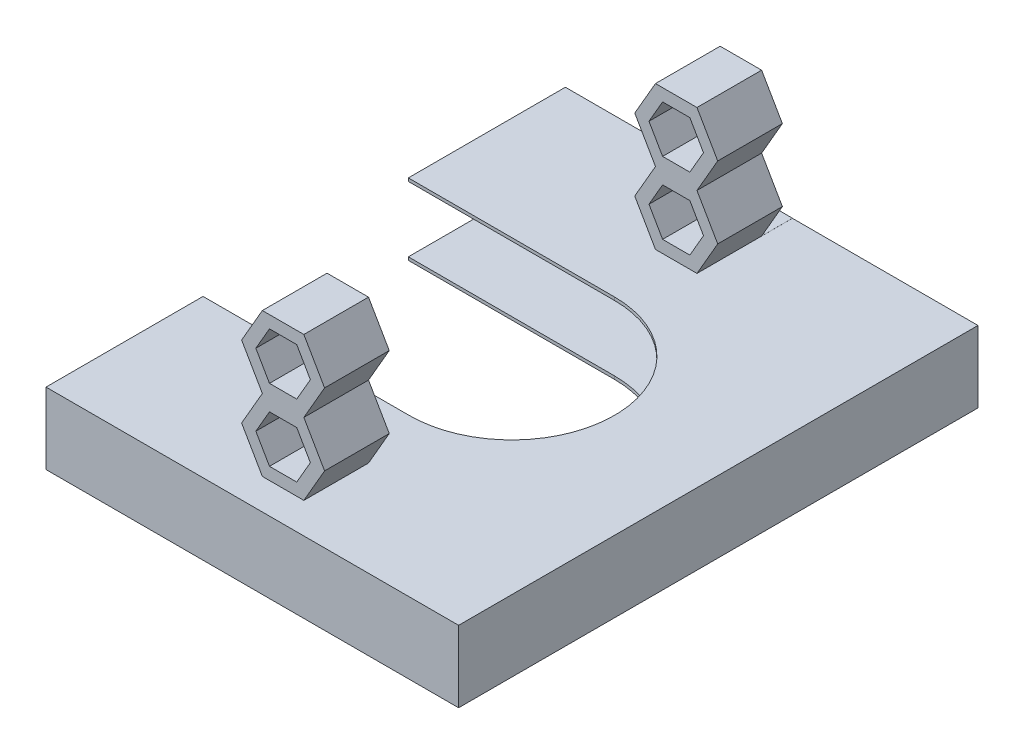
SolidWorks part; units mm, degrees
ref_plane "Front Plane" through (0, 0, 0) normal (0, 0, 1) x (1, 0, 0)
ref_plane "Top Plane" through (0, 0, 0) normal (0, 1, 0) x (1, 0, 0)
ref_plane "Right Plane" through (0, 0, 0) normal (1, 0, 0) x (0, 0, -1)
sketch "Sketch2" plane through (0, 0, 0) normal (0, 0, 1) x (1, 0, 0)
  line L0 (3.0311, 2.5013) -> (4.0415, 2.5013)
  line L1 (4.0415, 4.2513) -> (3.0311, 6.0013)
  line L2 (0, 0) -> (4.0415, 0)
  line L3 (0, 0) -> (0, 2.5013)
  line L4 (0, 2.5013) -> (1.0104, 2.5013)
  line L5 (4.0415, 0) -> (4.0415, 2.5013)
  line L7 (1.0104, 6.0013) -> (0, 4.2513)
  line L8 (0, 4.2513) -> (1.0104, 2.5013)
  line L10 (3.0311, 2.5013) -> (4.0415, 4.2513)
  line L11 (4.0415, 7.7513) -> (3.0311, 9.5013)
  line L12 (3.0311, 9.5013) -> (1.0104, 9.5013)
  line L13 (1.0104, 9.5013) -> (0, 7.7513)
  line L14 (0, 7.7513) -> (1.0104, 6.0013)
  line L16 (3.0311, 6.0013) -> (4.0415, 7.7513)
  line L17 (2.0207, 6.0013) -> (3.0311, 6.0013) [skipped]
  line L18 (3.0311, 6.0013) -> (2.0207, 6.0013) [skipped]
  line L19 (2.0207, 2.5013) -> (3.0311, 2.5013) [skipped]
  circle A0 centre (2.0207, 4.2513) radius 1.75 construction
  circle A1 centre (2.0207, 7.7513) radius 1.75 construction
extrude "Boss-Extrude1" add sketch "Sketch2" along normal blind 25.3 contours L1 L16 L11 L12 L13 L14 L7 L8 L4 L3 L2 L5 L0 L10
sketch "Sketch3" plane through (0, 0, 25.3) normal (0, 0, 1) x (1, 0, 0)
  line L0 (1.0104, 9.5013) -> (0, 7.7513) construction
  line L1 (3.3486, 7.7513) -> (2.6847, 8.9013)
  line L2 (2.6847, 8.9013) -> (1.3568, 8.9013)
  line L3 (1.3568, 8.9013) -> (0.6928, 7.7513)
  line L4 (0.6928, 7.7513) -> (1.3568, 6.6013)
  line L5 (1.3568, 6.6013) -> (2.6847, 6.6013)
  line L6 (2.6847, 6.6013) -> (3.3486, 7.7513)
  line L7 (3.0311, 6.0013) -> (4.0415, 7.7513) construction
  line L8 (4.0415, 7.7513) -> (3.0311, 9.5013) construction
  line L11 (3.3486, 4.2513) -> (2.6847, 5.4013)
  line L12 (2.6847, 5.4013) -> (1.3568, 5.4013)
  line L13 (1.3568, 5.4013) -> (0.6928, 4.2513)
  line L14 (0.6928, 4.2513) -> (1.3568, 3.1013)
  line L15 (1.3568, 3.1013) -> (2.6847, 3.1013)
  line L16 (2.6847, 3.1013) -> (3.3486, 4.2513)
  line L17 (1.0104, 6.0013) -> (0, 4.2513) construction
  line L18 (0, 4.2513) -> (1.0104, 2.5013) construction
  line L19 (4.0415, 4.2513) -> (3.0311, 6.0013) construction
  circle A0 centre (2.0207, 7.7513) radius 1.15 construction
  circle A1 centre (2.0207, 4.2513) radius 1.15 construction
  dimension "D1" = 0.6
  dimension "D2" = 0.6
  dimension "D3" = 0.6
  dimension "D4" = 0.6
  dimension "D5" = 0.6
  dimension "D6" = 0.6
extrude "Cut-Extrude1" cut sketch "Sketch3" against normal blind 25.3
sketch "Sketch14" plane through (0, 0, 0) normal (0, 0, -1) x (-1, 0, 0)
  line L1 (-4.2364, 9.6861) -> (0.2393, 9.6861)
  line L2 (-4.2364, 9.6861) -> (-4.2364, 2.5073)
  line L3 (-4.2364, 2.5073) -> (0.2393, 2.5073)
  line L4 (0.2393, 9.6861) -> (0.2393, 2.5073)
extrude "Cut-Extrude6" cut sketch "Sketch14" against normal blind 1.5
sketch "Sketch15" plane through (0, 0, 25.3) normal (0, 0, 1) x (1, 0, 0)
  line L1 (0, 9.6086) -> (4.0415, 9.6086)
  line L2 (0, 9.6086) -> (0, 2.5013)
  line L3 (0, 2.5013) -> (4.0415, 2.5013)
  line L4 (4.0415, 9.6086) -> (4.0415, 2.5013)
extrude "Cut-Extrude7" cut sketch "Sketch15" against normal blind 1.5
sketch "Sketch16" plane through (0, 9.5013, 0) normal (0, 1, 0) x (1, 0, 0)
  line L1 (-0.7522, -4.65) -> (4.5577, -4.65)
  line L2 (-0.7522, -4.65) -> (-0.7522, -20.65)
  line L3 (-0.7522, -20.65) -> (4.5577, -20.65)
  line L4 (4.5577, -4.65) -> (4.5577, -20.65)
  line L6 (1.0104, -1.5) -> (3.0311, -1.5) construction
  line L7 (3.0311, -23.8) -> (1.0104, -23.8) construction
  point P4 (1.9027, -4.65)
  dimension "D1" = 16
  dimension "D2" = 3.15
  dimension "D3" = 3.15
extrude "Cut-Extrude8" cut sketch "Sketch16" against normal blind 7
sketch "Sketch17" plane through (4.0415, 0, 0) normal (1, 0, 0) x (0, 0, -1)
  line L1 (-25.3, 2.5013) -> (0, 2.5013)
  line L2 (-25.3, 2.5013) -> (-25.3, 0)
  line L3 (-25.3, 0) -> (0, 0)
  line L4 (0, 2.5013) -> (0, 0)
extrude "Boss-Extrude2" add sketch "Sketch17" along normal blind 8.0293
sketch "Sketch18" plane through (0, 0, 0) normal (-1, 0, 0) x (0, 0, 1)
  line L1 (0, 0) -> (25.3, 0)
  line L2 (0, 0) -> (0, 2.5013)
  line L3 (0, 2.5013) -> (25.3, 2.5013)
  line L4 (25.3, 0) -> (25.3, 2.5013)
extrude "Boss-Extrude3" add sketch "Sketch18" along normal blind 8.0293
sketch "Sketch20" plane through (0, 0, 0) normal (0, -1, 0) x (1, 0, 0)
  line L1 (-8.0293, 0) -> (12.0707, 0)
  line L2 (-8.0293, 0) -> (-8.0293, 25.3)
  line L3 (-8.0293, 25.3) -> (12.0707, 25.3)
  line L4 (12.0707, 0) -> (12.0707, 25.3)
extrude "Boss-Extrude4" add sketch "Sketch20" along normal blind 0.9787
sketch "Sketch21" plane through (0, 2.5013, 0) normal (0, 1, 0) x (1, 0, 0)
  line L2 (-8.0293, -25.3) -> (-8.0293, 0) construction
  line L3 (-8.0293, -7.65) -> (2.0107, -7.65)
  line L4 (-8.0293, -7.65) -> (-8.0293, -17.65)
  line L5 (-8.0293, -17.65) -> (2.0107, -17.65)
  arc A0 (2.0107, -17.65) -> (2.0107, -7.65) centre (2.0107, -12.65) ccw
extrude "Cut-Extrude9" cut sketch "Sketch21" against normal blind 3.48 contours A0 L3 L4 L5
sketch "Sketch22" plane through (-8.0293, 0, 0) normal (-1, 0, 0) x (0, 0, 1)
  line L0 (7.65, 2.5013) -> (0, 2.5013) construction
  line L1 (0.15, -0.8287) -> (25.15, -0.8287)
  line L2 (0.15, -0.8287) -> (0.15, 2.3513)
  line L3 (0.15, 2.3513) -> (25.15, 2.3513)
  line L4 (25.15, -0.8287) -> (25.15, 2.3513)
  line L5 (0, 2.5013) -> (0, -0.9787) construction
  dimension "D1" = 25
  dimension "D2" = 3.18
  dimension "D3" = 0.15
  dimension "D4" = 0.15
extrude "Cut-Extrude10" cut sketch "Sketch22" against normal blind 19.8
